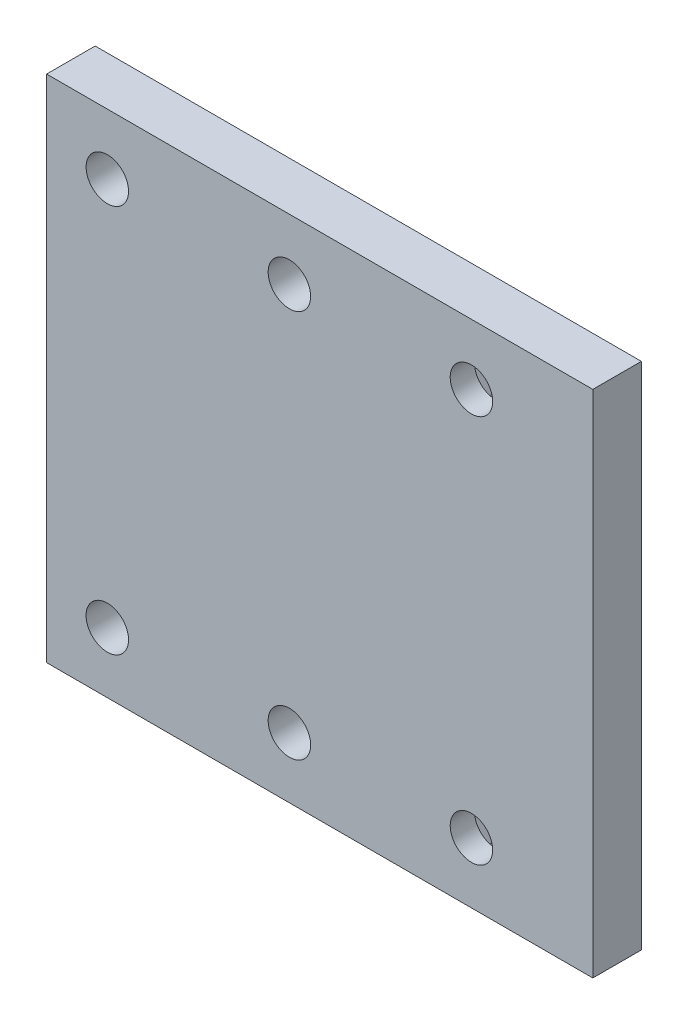
SolidWorks part; units mm, degrees
ref_plane "Front Plane" through (0, 0, 0) normal (0, 0, 1) x (1, 0, 0)
ref_plane "Top Plane" through (0, 0, 0) normal (0, 1, 0) x (1, 0, 0)
ref_plane "Right Plane" through (0, 0, 0) normal (1, 0, 0) x (0, 0, -1)
sketch "Sketch1" plane through (0, 0, 0) normal (0, 0, 1) x (1, 0, 0)
  line L1 (-22.5, 21) -> (22.5, 21)
  line L2 (-22.5, 21) -> (-22.5, -21)
  line L3 (-22.5, -21) -> (22.5, -21)
  line L4 (22.5, 21) -> (22.5, -21)
  line L5 (-22.5, 21) -> (22.5, -21) construction
  line L6 (-22.5, -21) -> (22.5, 21) construction
  point P0 (0, 0)
  dimension "D1" = 42
  dimension "D2" = 45
extrude "Boss-Extrude1" add sketch "Sketch1" along normal blind 4
sketch "Sketch2" plane through (0, 0, 4) normal (0, 0, 1) x (1, 0, 0)
  line L0 (22.5, 21) -> (-22.5, 21) construction
  line L1 (-22.5, 21) -> (-22.5, -21) construction
  line L2 (-4.2002, 0) -> (0, 0) construction
  circle A0 centre (-17.5, 16) radius 1.75
  circle A1 centre (-2.5, 16) radius 1.75
  circle A2 centre (-2.5, -16) radius 1.75
  circle A3 centre (-17.5, -16) radius 1.75
  dimension "D1" = 3.5
  dimension "D4" = 3.5
  dimension "D2" = 5
  dimension "D3" = 5
  dimension "D5" = 15
extrude "Cut-Extrude1" cut sketch "Sketch2" against normal through all
sketch "Sketch3" plane through (0, 0, 4) normal (0, 0, 1) x (1, 0, 0)
  line L0 (3.2308, 0) -> (0, 0) construction
  line L1 (22.5, 21) -> (-22.5, 21) construction
  line L2 (22.5, -21) -> (22.5, 21) construction
  circle A0 centre (12.5, 16) radius 1.75
  circle A1 centre (12.5, -16) radius 1.75
  dimension "D1" = 3.5
  dimension "D2" = 5
  dimension "D3" = 10
extrude "Cut-Extrude2" cut sketch "Sketch3" against normal through all
sketch "Sketch5" plane through (0, 0, 0) normal (0, 0, -1) x (-1, 0, 0)
  line L0 (-5.2037, 0) -> (0, 0) construction
  line L1 (-9.2091, -16) -> (-10.8546, -13.15)
  line L2 (-10.8546, -13.15) -> (-14.1454, -13.15)
  line L3 (-14.1454, -13.15) -> (-15.7909, -16)
  line L4 (-15.7909, -16) -> (-14.1454, -18.85)
  line L5 (-14.1454, -18.85) -> (-10.8546, -18.85)
  line L6 (-10.8546, -18.85) -> (-9.2091, -16)
  line L7 (-10.8546, 18.85) -> (-9.2091, 16)
  line L8 (-14.1454, 18.85) -> (-10.8546, 18.85)
  line L9 (-15.7909, 16) -> (-14.1454, 18.85)
  line L10 (-14.1454, 13.15) -> (-15.7909, 16)
  line L11 (-10.8546, 13.15) -> (-14.1454, 13.15)
  line L12 (-9.2091, 16) -> (-10.8546, 13.15)
  circle A0 centre (-12.5, -16) radius 2.85 construction
  circle A1 centre (-12.5, 16) radius 2.85 construction
  dimension "D1" = 5.7
extrude "Cut-Extrude4" cut sketch "Sketch5" against normal blind 2
